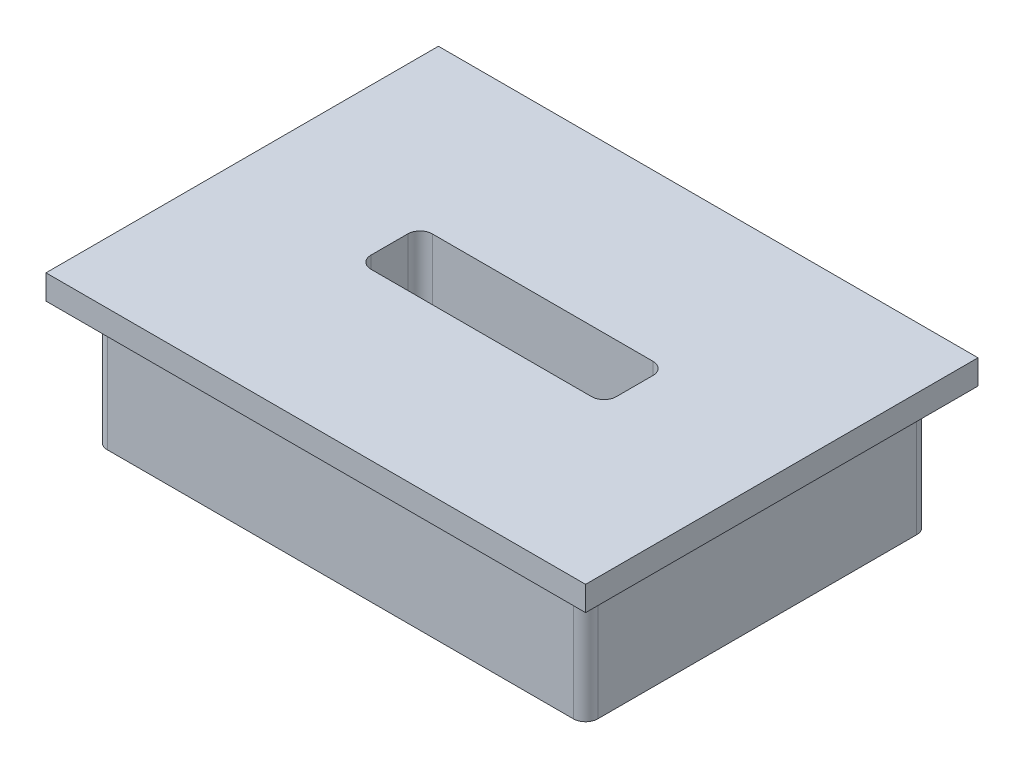
SolidWorks part; units mm, degrees
ref_plane "Front Plane" through (0, 0, 0) normal (0, 0, 1) x (1, 0, 0)
ref_plane "Top Plane" through (0, 0, 0) normal (0, 1, 0) x (1, 0, 0)
ref_plane "Right Plane" through (0, 0, 0) normal (1, 0, 0) x (0, 0, -1)
sketch "Sketch1" plane through (0, 0, 0) normal (0, 1, 0) x (1, 0, 0)
  line L1 (0, 0) -> (20, 0)
  line L2 (0, 0) -> (0, -14)
  line L3 (0, -14) -> (20, -14)
  line L4 (20, 0) -> (20, -14)
  line L6 (5, -8.25) -> (15, -8.25)
  line L7 (5, -5.75) -> (15, -5.75)
  line L8 (5, -5.75) -> (5, -8.25)
  line L9 (15, -5.75) -> (15, -8.25)
  dimension "D3" = 10
  dimension "D1" = 20
  dimension "D2" = 14
  dimension "D4" = 2.5
  dimension "D5" = 5.75
  dimension "D6" = 5
extrude "Boss-Extrude1" add sketch "Sketch1" along normal blind 5
sketch "Sketch2" plane through (0, 5, 0) normal (0, 1, 0) x (1, 0, 0)
  line L0 (0, 0) -> (0, -14) construction
  line L1 (-1, 1) -> (21, 1)
  line L2 (-1, 1) -> (-1, -15)
  line L3 (-1, -15) -> (21, -15)
  line L4 (21, 1) -> (21, -15)
  line L5 (0, -14) -> (20, -14) construction
  line L7 (5, -5.75) -> (15, -5.75)
  line L8 (5, -5.75) -> (5, -8.25)
  line L9 (5, -8.25) -> (15, -8.25)
  line L10 (15, -5.75) -> (15, -8.25)
  dimension "D1" = 22
  dimension "D2" = 16
  dimension "D3" = 1
  dimension "D4" = 1
extrude "Boss-Extrude2" add sketch "Sketch2" along normal blind 1
fillet "Fillet1" radius 0.5 8 edges at (5, 3, 5.75) (15, 3, 5.75) (5, 3, 8.25) (15, 3, 8.25) (20, 2.5, 0) (0, 2.5, 0) (0, 2.5, 14) (20, 2.5, 14)
